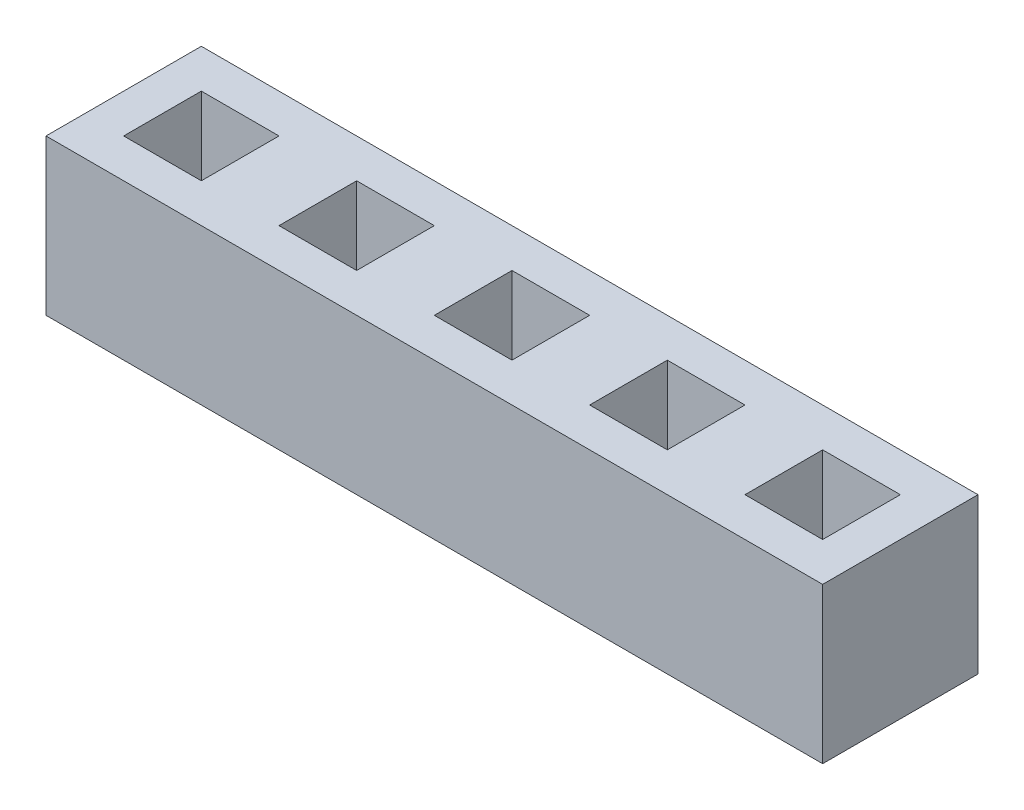
SolidWorks part; units mm, degrees
material "PVC 0.007 Plasticized"
ref_plane "Front Plane" through (0, 0, 0) normal (0, 0, 1) x (1, 0, 0)
ref_plane "Top Plane" through (0, 0, 0) normal (0, 1, 0) x (1, 0, 0)
ref_plane "Right Plane" through (0, 0, 0) normal (1, 0, 0) x (0, 0, -1)
sketch "Sketch1" plane through (0, 0, 0) normal (0, 1, 0) x (1, 0, 0)
  line L0 (4.445, 1.905) -> (4.445, 0.635)
  line L1 (0, 0) -> (12.7, 0)
  line L2 (0, 0) -> (0, 2.54)
  line L3 (0, 2.54) -> (12.7, 2.54)
  line L4 (12.7, 0) -> (12.7, 2.54)
  line L5 (0.635, 1.905) -> (1.905, 1.905)
  line L6 (0.635, 1.905) -> (0.635, 0.635)
  line L7 (0.635, 0.635) -> (1.905, 0.635)
  line L8 (1.905, 1.905) -> (1.905, 0.635)
  line L9 (3.175, 1.905) -> (4.445, 1.905)
  line L10 (3.175, 1.905) -> (3.175, 0.635)
  line L11 (3.175, 0.635) -> (4.445, 0.635)
  line L12 (6.985, 1.905) -> (6.985, 0.635)
  line L13 (5.715, 1.905) -> (6.985, 1.905)
  line L14 (5.715, 1.905) -> (5.715, 0.635)
  line L15 (5.715, 0.635) -> (6.985, 0.635)
  line L16 (9.525, 1.905) -> (9.525, 0.635)
  line L17 (8.255, 1.905) -> (9.525, 1.905)
  line L18 (8.255, 1.905) -> (8.255, 0.635)
  line L19 (8.255, 0.635) -> (9.525, 0.635)
  line L20 (12.065, 1.905) -> (12.065, 0.635)
  line L21 (10.795, 1.905) -> (12.065, 1.905)
  line L22 (10.795, 1.905) -> (10.795, 0.635)
  line L23 (10.795, 0.635) -> (12.065, 0.635)
  dimension "D1" = 12.7
  dimension "D2" = 2.54
  dimension "D3" = 1.27
  dimension "D4" = 1.27
  dimension "D5" = 0.635
  dimension "D6" = 0.635
  dimension "D7" = 5
extrude "Boss-Extrude1" add sketch "Sketch1" along normal blind 2.54
